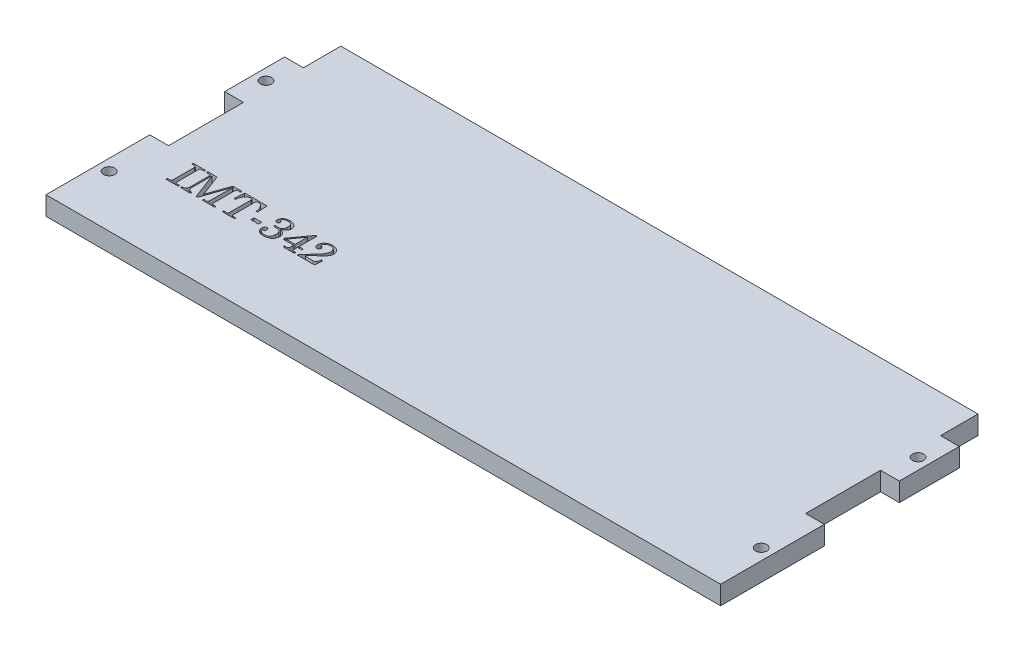
SolidWorks part; units mm, degrees
material "Trupan"
ref_plane "Alzado" through (0, 0, 0) normal (0, 0, 1) x (1, 0, 0)
ref_plane "Planta" through (0, 0, 0) normal (0, 1, 0) x (1, 0, 0)
ref_plane "Vista lateral" through (0, 0, 0) normal (1, 0, 0) x (0, 0, -1)
sketch "Croquis1" plane through (0, 0, 0) normal (0, 1, 0) x (1, 0, 0)
  line L1 (90, -8) -> (-90, -8)
  line L2 (90, -8) -> (90, 8)
  line L3 (90, 8) -> (-90, 8)
  line L4 (-90, -8) -> (-90, 8)
  line L5 (90, -8) -> (-90, 8) construction
  line L6 (90, 8) -> (-90, -8) construction
  line L7 (85, -28) -> (-85, -28)
  line L8 (85, -28) -> (85, -8)
  line L9 (85, -8) -> (-85, -8)
  line L10 (-85, -28) -> (-85, -8)
  line L11 (85, -28) -> (-85, -8) construction
  line L12 (85, -8) -> (-85, -28) construction
  line L13 (90, -55.68) -> (-90, -55.68)
  line L14 (90, -55.68) -> (90, -28)
  line L15 (90, -28) -> (-90, -28)
  line L16 (-90, -55.68) -> (-90, -28)
  line L17 (90, -55.68) -> (-90, -28) construction
  line L18 (90, -28) -> (-90, -55.68) construction
  point P0 (0, 0)
  point P6 (0, -18)
  point P11 (0, -41.84)
  point P16 (0, -8)
  dimension "D1" = 16
  dimension "D2" = 180
  dimension "D3" = 170
  dimension "D4" = 20
  dimension "D5" = 27.68
  dimension "D6" = 180
extrude "Saliente-Extruir1" add sketch "Croquis1" along normal blind 5 contours L16 L13 L14 L15 L7 | L10 L7 L8 L1 | L4 L1 L2 L3
sketch "Croquis2" plane through (0, 5, 0) normal (0, 1, 0) x (1, 0, 0)
  line L0 (-90, -8) -> (-90, 8) construction
  line L1 (-90, -55.68) -> (-90, -28) construction
  circle A0 centre (-87, 0) radius 1.5
  circle A1 centre (-87, -41.84) radius 1.5
  dimension "D1" = 3
  dimension "D2" = 3
  dimension "D3" = 3
  dimension "D4" = 3
extrude "Cortar-Extruir1" cut sketch "Croquis2" against normal through all
mirror "Simetría1" about plane through (0, 0, 0) normal (1, 0, 0) of "Cortar-Extruir1"
sketch "Croquis3" plane through (0, 5, 0) normal (0, 1, 0) x (1, 0, 0)
  line L0 (90, 8) -> (-90, 8) construction
  line L1 (85, 23) -> (-85, 23)
  line L2 (85, 23) -> (85, 8)
  line L3 (85, 8) -> (-85, 8)
  line L4 (-85, 23) -> (-85, 8)
  line L5 (85, 23) -> (-85, 8) construction
  line L6 (85, 8) -> (-85, 23) construction
  point P0 (0, 15.5)
  dimension "D1" = 170
  dimension "D2" = 15
extrude "Saliente-Extruir2" add sketch "Croquis3" against normal blind 5
sketch "Croquis4" plane through (0, 5, 0) normal (0, 1, 0) x (1, 0, 0)
  line L0 (-85, -36.0778) -> (-30.3468, -36.0778) construction
  text T0 "IMT-342" font "Century Schoolbook" height in points 28
extrude "Cortar-Extruir3" cut sketch "Croquis4" against normal through all
sketch "Croquis5" plane through (0, 5, 0) normal (0, 1, 0) x (1, 0, 0)
  line L0 (85, 8) -> (85, 23) construction
  line L1 (-85, 23) -> (85, 23)
  line L2 (-85, 23) -> (-85, 18)
  line L3 (-85, 18) -> (85, 18)
  line L4 (85, 23) -> (85, 18)
  dimension "D1" = 5
extrude "Cortar-Extruir4" cut sketch "Croquis5" against normal through all
